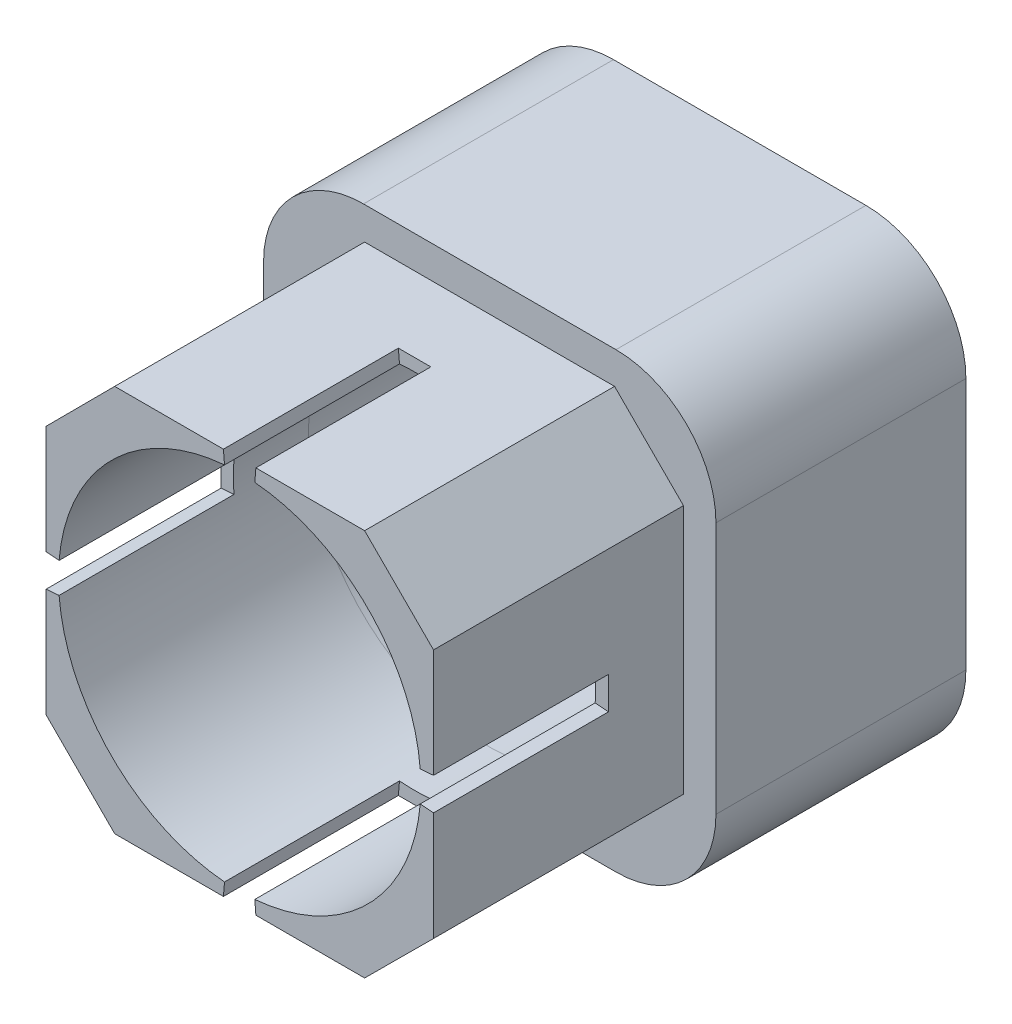
SolidWorks part; units mm, degrees
ref_plane "Front Plane" through (0, 0, 0) normal (0, 0, 1) x (1, 0, 0)
ref_plane "Top Plane" through (0, 0, 0) normal (0, 1, 0) x (1, 0, 0)
ref_plane "Right Plane" through (0, 0, 0) normal (1, 0, 0) x (0, 0, -1)
sketch "Sketch1" plane through (0, 0, 0) normal (0, 0, 1) x (1, 0, 0)
  line L0 (-5.05, 9.05) -> (5.05, 9.05)
  line L1 (9.05, -5.05) -> (9.05, 5.05)
  line L2 (0, 0) -> (0, 14.1446) construction
  line L3 (-9.05, -5.05) -> (-9.05, 5.05)
  line L4 (-12.732, 0) -> (15.0845, 0) construction
  line L5 (-5.05, -9.05) -> (5.05, -9.05)
  arc A4 (5.05, 9.05) -> (9.05, 5.05) centre (5.05, 5.05) cw
  arc A5 (9.05, -5.05) -> (5.05, -9.05) centre (5.05, -5.05) cw
  arc A6 (-5.05, -9.05) -> (-9.05, -5.05) centre (-5.05, -5.05) cw
  arc A7 (-9.05, 5.05) -> (-5.05, 9.05) centre (-5.05, 5.05) cw
  point P11 (9.05, 0)
  point P12 (0, 9.05)
  point P20 (0, -9.05)
  point P21 (-9.05, 0)
  dimension "D3" = 0
  dimension "D1" = 5.05
  dimension "D2" = 5.05
  dimension "D4" = 9.05
  dimension "D5" = 9.05
extrude "Boss-Extrude1" add sketch "Sketch1" along normal blind 10
sketch "Sketch22" plane through (0, 0, 10) normal (0, 0, 1) x (1, 0, 0)
  line L0 (-5.0065, -7.75) -> (4.9935, -7.75)
  line L1 (-7.75, -5.0039) -> (-7.75, 4.9961)
  line L2 (-5.0065, 7.75) -> (4.9935, 7.75)
  line L3 (7.75, -5.0039) -> (7.75, 4.9961)
  line L4 (4.9935, 7.75) -> (7.75, 4.9961)
  line L5 (-5.0065, 7.75) -> (-7.75, 4.9961)
  line L10 (-5.0065, -7.75) -> (-7.75, -5.0039)
  line L11 (4.9935, -7.75) -> (7.75, -5.0039)
  circle A0 centre (-0.0065, 0) radius 7.25
  dimension "D2" = 14.5
  dimension "D1" = 7.75
  dimension "D3" = 7.75
  dimension "D4" = 7.75
  dimension "D5" = 7.75
  dimension "D6" = 0
extrude "Boss-Extrude4" add sketch "Sketch22" along normal blind 10
sketch "Sketch24" plane through (0, 0, 10) normal (0, 0, 1) x (1, 0, 0)
  circle A1 centre (0, 0) radius 7.2565
extrude "Cut-Extrude15" cut sketch "Sketch24" against normal blind 35
sketch "Sketch25" plane through (0, 0, 20) normal (0, 0, 1) x (1, 0, 0)
  line L0 (0, 0) -> (7.75, 0.65)
  line L1 (7.75, -5.0039) -> (7.75, 4.9961) construction
  line L2 (7.75, 0.65) -> (7.75, -0.65)
  line L3 (7.75, -0.65) -> (0, 0)
  dimension "D1" = 0.65
  dimension "D2" = 0.65
extrude "Cut-Extrude16" cut sketch "Sketch25" against normal blind 7
pattern_circular "CirPattern1" count 4 every 90 about axis through (-0.0065, 0, 20) along (0, 0, -1) of "Cut-Extrude16"
